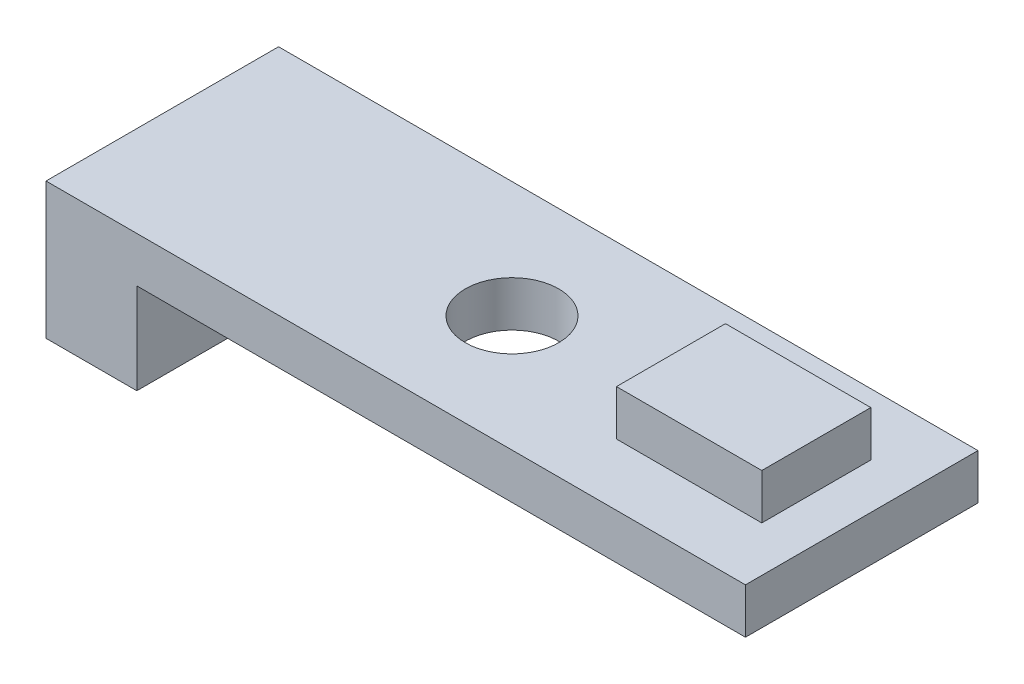
SolidWorks part; units mm, degrees
ref_plane "Front Plane" through (0, 0, 0) normal (0, 0, 1) x (1, 0, 0)
ref_plane "Top Plane" through (0, 0, 0) normal (0, 1, 0) x (1, 0, 0)
ref_plane "Right Plane" through (0, 0, 0) normal (1, 0, 0) x (0, 0, -1)
sketch "Sketch1" plane through (0, 0, 0) normal (0, 1, 0) x (1, 0, 0)
  line L1 (-12.2238, -4.064) -> (12.2238, -4.064)
  line L2 (-12.2238, -4.064) -> (-12.2238, 4.064)
  line L3 (-12.2238, 4.064) -> (12.2238, 4.064)
  line L4 (12.2238, -4.064) -> (12.2238, 4.064)
  line L5 (-12.2238, -4.064) -> (12.2238, 4.064) construction
  line L6 (-12.2238, 4.064) -> (12.2238, -4.064) construction
  circle A0 centre (0, 0) radius 1.632
  point P0 (0, 0)
  dimension "D3" = 3.2639
  dimension "D1" = 24.4475
  dimension "D2" = 8.128
extrude "Boss-Extrude1" add sketch "Sketch1" along normal blind 1.5875
sketch "Sketch2" plane through (0, 1.5875, 0) normal (0, 1, 0) x (1, 0, 0)
  line L0 (0, 0) -> (50000, 0) construction
  line L1 (12.2238, -4.064) -> (12.2238, 4.064) construction
  line L2 (5.5562, -1.905) -> (10.6363, -1.905)
  line L3 (5.5562, -1.905) -> (5.5562, 1.905)
  line L4 (5.5562, 1.905) -> (10.6362, 1.905)
  line L5 (10.6363, -1.905) -> (10.6362, 1.905)
  line L6 (5.5562, -1.905) -> (10.6362, 1.905) construction
  line L7 (5.5562, 1.905) -> (10.6363, -1.905) construction
  point P3 (8.0962, 0)
  dimension "D1" = 3.81
  dimension "D2" = 5.08
  dimension "D3" = 1.5875
extrude "Boss-Extrude2" add sketch "Sketch2" along normal blind 1.5875
sketch "Sketch3" plane through (0, 0, 0) normal (0, -1, 0) x (1, 0, 0)
  line L0 (12.2238, -4.064) -> (-12.2238, -4.064) construction
  line L1 (-12.2238, 4.064) -> (-9.0488, 4.064)
  line L2 (-12.2238, 4.064) -> (-12.2238, -4.064)
  line L3 (-12.2238, -4.064) -> (-9.0488, -4.064)
  line L4 (-9.0488, 4.064) -> (-9.0488, -4.064)
  dimension "D1" = 3.175
extrude "Boss-Extrude3" add sketch "Sketch3" along normal blind 3.175
